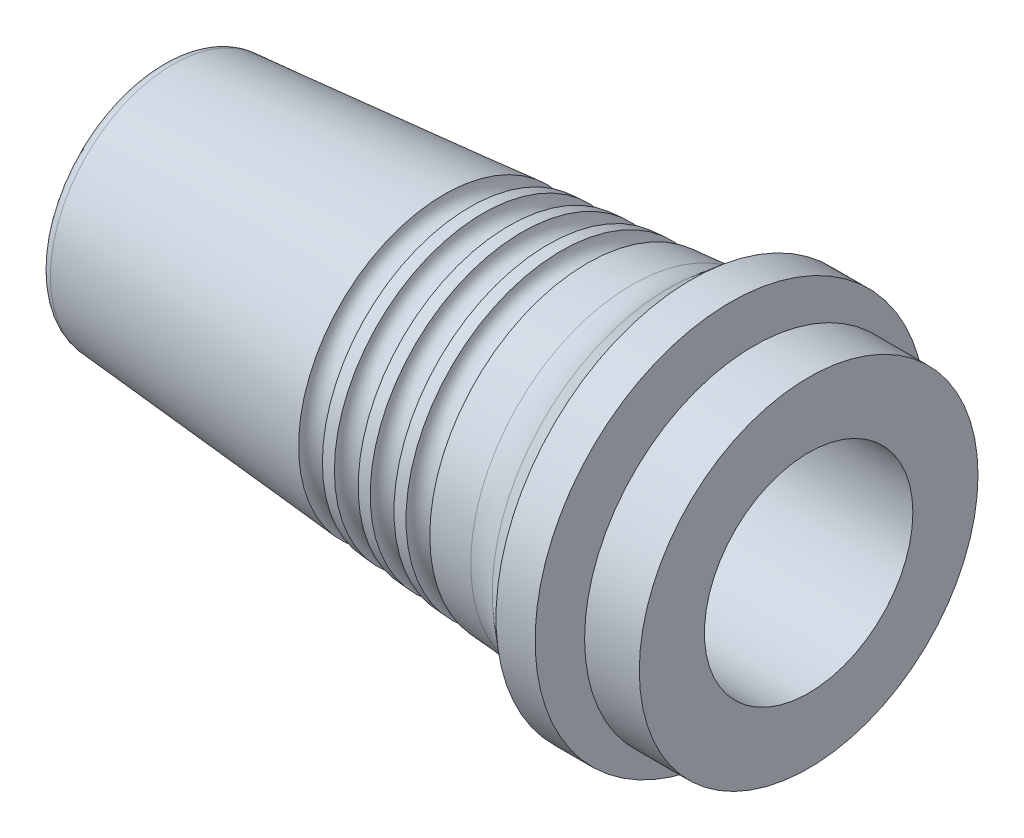
SolidWorks part; units mm, degrees
material "ABS"
ref_plane "Front Plane" through (0, 0, 0) normal (0, 0, 1) x (1, 0, 0)
ref_plane "Top Plane" through (0, 0, 0) normal (0, 1, 0) x (1, 0, 0)
ref_plane "Right Plane" through (0, 0, 0) normal (1, 0, 0) x (0, 0, -1)
sketch "Sketch1" plane through (0, 0, 0) normal (0, 0, 1) x (1, 0, 0)
  line L0 (44.8671, 0) -> (-44.8671, 0) construction
  line L1 (-24.3783, 9.3651) -> (-2.9965, 11.1584)
  line L3 (19, 15) -> (19, 10)
  line L4 (19, 10) -> (20.8, 10)
  line L6 (25, 8) -> (-25, 8)
  line L7 (-25, 8) -> (-24.3783, 9.3651)
  line L8 (0, 8) -> (0, 0) construction
  line L9 (13, 12.5) -> (19, 12.5) construction
  line L10 (19, 15) -> (16, 15)
  line L11 (16, 15) -> (13, 12.5)
  line L12 (-1.0035, 11.3255) -> (0.0035, 11.41)
  line L13 (1.9965, 11.5771) -> (3.0035, 11.6616)
  line L14 (4.9965, 11.8288) -> (6.0035, 11.9132)
  line L15 (7.9965, 12.0804) -> (13, 12.5)
  line L16 (20.8, 10) -> (20.8, 13)
  line L17 (20.8, 13) -> (25, 13)
  line L19 (25, 13) -> (25, 8)
  arc A0 (6.0035, 11.9132) -> (7.9965, 12.0804) centre (7, 11.9968) ccw
  arc A1 (3.0035, 11.6616) -> (4.9965, 11.8288) centre (4, 11.7452) ccw
  arc A2 (0.0035, 11.41) -> (1.9965, 11.5771) centre (1, 11.4936) ccw
  arc A3 (-2.9965, 11.1584) -> (-1.0035, 11.3255) centre (-2, 11.242) ccw
  point P4 (0, 0)
  point P10 (-2, 11.3255)
  dimension "D9" = 2
  dimension "D11" = 2
  dimension "D13" = 2
  dimension "D15" = 2
  dimension "D1" = 16
  dimension "D2" = 20
  dimension "D3" = 6
  dimension "D4" = 1.5
  dimension "D5" = 4.2
  dimension "D6" = 6
  dimension "D7" = 3
  dimension "D8" = 5
  dimension "D10" = 6
  dimension "D12" = 3
  dimension "D14" = 3
  dimension "D16" = 3
  dimension "D17" = 50
  dimension "D18" = 26
revolve "Revolve1" add sketch "Sketch1" angle 360 about L0
fillet "Fillet1" radius 1 1 edges at (-24.3783, 0, -9.3651)
fillet "Fillet2" radius 5 1 edges at (13, 0, -12.5)
